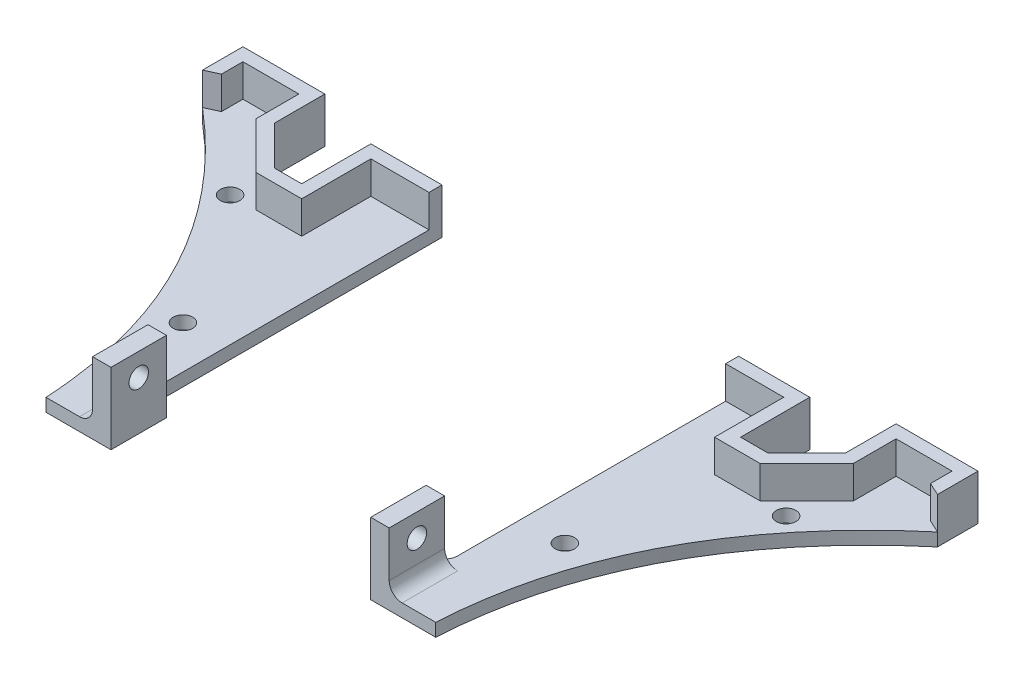
SolidWorks part; units mm, degrees
ref_plane "Front Plane" through (0, 0, 0) normal (0, 0, 1) x (1, 0, 0)
ref_plane "Top Plane" through (0, 0, 0) normal (0, 1, 0) x (1, 0, 0)
ref_plane "Right Plane" through (0, 0, 0) normal (1, 0, 0) x (0, 0, -1)
sketch "Sketch1" plane through (0, 0, 0) normal (0, 1, 0) x (1, 0, 0)
  line L0 (-56.5883, 22.2246) -> (-56.5883, 28.4551)
  line L1 (-22.8361, -28.4551) -> (-30, -28.4551)
  line L2 (-43.9759, 28.4551) -> (-56.5883, 28.4551)
  line L6 (-37.9759, 14.6993) -> (-33.7879, 14.6993)
  line L7 (-43.9759, 20.6993) -> (-37.9759, 14.6993)
  line L8 (-43.9759, 20.6993) -> (-43.9759, 28.4551)
  line L21 (-22.8361, -28.4551) -> (-22.8361, 25.3517)
  line L22 (-33.7879, 25.3517) -> (-22.8361, 25.3517)
  line L23 (-33.7879, 25.3517) -> (-33.7879, 14.6993)
  line L24 (0, -55) -> (0, 55) construction
  line L25 (33.7879, 25.3517) -> (33.7879, 14.6993)
  line L26 (33.7879, 25.3517) -> (22.8361, 25.3517)
  line L27 (22.8361, -28.4551) -> (22.8361, 25.3517)
  line L28 (43.9759, 20.6993) -> (43.9759, 28.4551)
  line L29 (43.9759, 20.6993) -> (37.9759, 14.6993)
  line L30 (37.9759, 14.6993) -> (33.7879, 14.6993)
  line L31 (43.9759, 28.4551) -> (56.5883, 28.4551)
  line L32 (22.8361, -28.4551) -> (30, -28.4551)
  line L33 (56.5883, 22.2246) -> (56.5883, 28.4551)
  parabola Q0 (30, -28.4551) -> (56.5883, 22.2246) focus (64.3146, -20.2927) apex (33.8007, -9.3631)
  parabola Q1 (-30, -28.4551) -> (-56.5883, 22.2246) focus (-64.3146, -20.2927) apex (-33.8007, -9.3631)
extrude "Boss-Extrude1" add sketch "Sketch1" along normal blind 2
sketch "Sketch2" plane through (0, 2, 0) normal (0, 1, 0) x (1, 0, 0)
  line L87 (-54.5883, 23.1453) -> (-56.5883, 22.2246)
  line L88 (-56.5883, 28.4551) -> (-56.5883, 22.2246) construction
  line L89 (-31.7879, 23.3517) -> (-22.8361, 23.3517)
  line L91 (-22.8361, 25.3517) -> (-33.7879, 25.3517) construction
  line L92 (-33.7879, 25.3517) -> (-33.7879, 14.6993) construction
  line L93 (-33.7879, 14.6993) -> (-37.9759, 14.6993) construction
  line L94 (-37.9759, 14.6993) -> (-43.9759, 20.6993) construction
  line L95 (-43.9759, 20.6993) -> (-43.9759, 28.4551) construction
  line L96 (-24.8361, 23.3517) -> (-31.7879, 23.3517)
  line L97 (-31.7879, 23.3517) -> (-31.7879, 12.6993)
  line L102 (-31.7879, 12.6993) -> (-38.8044, 12.6993)
  line L103 (-38.8044, 12.6993) -> (-45.9759, 19.8708)
  line L104 (-45.9759, 19.8708) -> (-45.9759, 26.4551)
  line L105 (-45.9759, 26.4551) -> (-54.5883, 26.4551)
  line L106 (-54.5883, 26.4551) -> (-54.5883, 23.1453)
  line L107 (-28.1314, -26.4551) -> (-24.8361, -26.4551)
  line L108 (-24.8361, -26.4551) -> (-24.8361, 23.3517)
  line L110 (-31.7879, 23.3517) -> (-31.7879, 12.6993)
  line L111 (-31.7879, 12.6993) -> (-38.8044, 12.6993)
  line L112 (-38.8044, 12.6993) -> (-45.9759, 19.8708)
  line L113 (-45.9759, 19.8708) -> (-45.9759, 26.4551)
  line L114 (-45.9759, 26.4551) -> (-54.5883, 26.4551)
  line L115 (-54.5883, 26.4551) -> (-54.5883, 23.1453)
  line L118 (-43.9759, 28.4551) -> (-56.5883, 28.4551) construction
  line L119 (-22.8361, 25.3517) -> (-33.7879, 25.3517)
  line L120 (-33.7879, 25.3517) -> (-33.7879, 14.6993)
  line L121 (-33.7879, 14.6993) -> (-37.9759, 14.6993)
  line L122 (-37.9759, 14.6993) -> (-43.9759, 20.6993)
  line L123 (-43.9759, 20.6993) -> (-43.9759, 28.4551)
  line L124 (-43.9759, 28.4551) -> (-56.5883, 28.4551)
  line L125 (-56.5883, 28.4551) -> (-56.5883, 22.2246)
  line L126 (-22.8361, -28.4551) -> (-22.8361, 25.3517) construction
  line L127 (-22.8361, 23.3517) -> (-22.8361, 25.3517)
  line L128 (0, -55) -> (0, 55) construction
  line L129 (22.8361, 23.3517) -> (22.8361, 25.3517)
  line L130 (56.5883, 28.4551) -> (56.5883, 22.2246)
  line L131 (43.9759, 28.4551) -> (56.5883, 28.4551)
  line L132 (43.9759, 20.6993) -> (43.9759, 28.4551)
  line L133 (37.9759, 14.6993) -> (43.9759, 20.6993)
  line L134 (33.7879, 14.6993) -> (37.9759, 14.6993)
  line L135 (33.7879, 25.3517) -> (33.7879, 14.6993)
  line L136 (22.8361, 25.3517) -> (33.7879, 25.3517)
  line L137 (54.5883, 26.4551) -> (54.5883, 23.1453)
  line L138 (45.9759, 26.4551) -> (54.5883, 26.4551)
  line L139 (45.9759, 19.8708) -> (45.9759, 26.4551)
  line L140 (38.8044, 12.6993) -> (45.9759, 19.8708)
  line L141 (31.7879, 12.6993) -> (38.8044, 12.6993)
  line L142 (31.7879, 23.3517) -> (31.7879, 12.6993)
  line L143 (31.7879, 23.3517) -> (22.8361, 23.3517)
  line L144 (54.5883, 23.1453) -> (56.5883, 22.2246)
  spline S0 degree 3 poles (355.549, 935.1677) (-543.6815, -23.2259) (-139.333, 126.3463) (-42.9049, 11.059) (-41.4488, 9.1514) (-39.4, 6.175) (-38.7396, 5.1636) (-37.4666, 3.1004) (-36.8533, 2.0468) (-33.9484, -3.2583) (-32.1105, -7.6699) (-30.0764, -14.5367) (-29.5188, -16.8672) (-28.8627, -20.425) (-28.674, -21.6221) (-7.5514, -182.2777) (-526.6137, -399.768) (895.9743, -408.5754) knots -7.464113 -7.464113 -7.464113 -7.464113 0.25 0.25 0.375 0.375 0.4375 0.4375 0.5 0.5 0.75 0.75 0.875 0.875 0.9375 0.9375 9.20233 9.20233 9.20233 9.20233 only from (-54.5883, 23.1453) to (-28.1314, -26.4551)
  dimension "D1" = 2
extrude "Boss-Extrude3" add sketch "Sketch2" along normal blind 5
sketch "Sketch3" plane through (0, 0, 0) normal (0, -1, 0) x (1, 0, 0)
  circle A0 centre (-29.4027, 7.9664) radius 1.5
  circle A1 centre (-42.8051, -12.6988) radius 1.5
  circle A2 centre (29.4027, 7.9664) radius 1.5
  circle A3 centre (42.8051, -12.6988) radius 1.5
extrude "Cut-Extrude1" cut sketch "Sketch3" against normal up to surface (2 mm away) up to face at (-40.8239, 2, -14.4257)
sketch "Sketch4" plane through (0, 2, 0) normal (0, 1, 0) x (1, 0, 0)
  line L0 (27.312, 18.6025) -> (27.312, 3.6025)
  line L1 (33.8053, 18.6025) -> (22.8327, 18.6025) construction
  line L3 (27.312, 3.6025) -> (22.8361, 3.6025)
  line L4 (22.8361, 23.3517) -> (22.8361, -28.4551) construction
  line L5 (22.8361, 3.6025) -> (22.8361, 18.6025)
  line L6 (22.8361, 18.6025) -> (27.312, 18.6025)
  dimension "D1" = 15
extrude "Cut-Extrude2" [suppressed] cut sketch "Sketch4" against normal up to surface (2 mm away)
sketch "Sketch5" plane through (0, 0, 0) normal (0, 1, 0) x (1, 0, 0)
  line L0 (0, -3.85) -> (0, 3.85) construction
  line L1 (-22.8361, -28.4551) -> (-19.9961, -28.4551)
  line L2 (-22.8361, -28.4551) -> (-22.8361, -19.9151)
  line L3 (-22.8361, -19.9151) -> (-19.9961, -19.9151)
  line L4 (-19.9961, -28.4551) -> (-19.9961, -19.9151)
  line L5 (19.9961, -28.4551) -> (19.9961, -19.9151)
  line L6 (22.8361, -19.9151) -> (19.9961, -19.9151)
  line L7 (22.8361, -28.4551) -> (22.8361, -19.9151)
  line L8 (22.8361, -28.4551) -> (19.9961, -28.4551)
  dimension "D1" = 2.84
  dimension "D2" = 8.54
extrude "Boss-Extrude4" add sketch "Sketch5" along normal blind 11
fillet "Fillet1" radius 2 1 edges at (-22.8361, 2, 24.1851)
fillet "Fillet2" radius 2 1 edges at (-22.8361, 1, 19.9151)
fillet "Fillet3" radius 2 1 edges at (22.8361, 2, 24.1851)
fillet "Fillet4" radius 2 1 edges at (22.8361, 1, 19.9151)
sketch "Sketch6" plane through (22.8361, 0, 0) normal (1, 0, 0) x (0, 0, -1)
  line L0 (-24.1851, 11) -> (-24.1851, 4) construction
  line L1 (-28.4551, 11) -> (-19.9151, 11) construction
  line L2 (-28.4551, 4) -> (-19.9151, 4) construction
  circle A0 centre (-24.1851, 7.5) radius 1.5
  dimension "D1" = 3
extrude "Cut-Extrude3" cut sketch "Sketch6" against normal up to surface (45.6723 mm away) contours A0 up to face at (-22.8361, 7.5, 24.1851)
